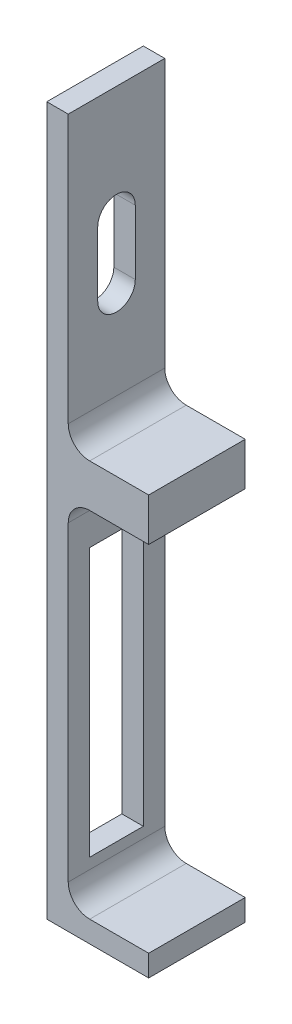
SolidWorks part; units mm, degrees
material "ПВХ Жесткий"
ref_plane "Спереди" through (0, 0, 0) normal (0, 0, 1) x (1, 0, 0)
ref_plane "Сверху" through (0, 0, 0) normal (0, 1, 0) x (1, 0, 0)
ref_plane "Справа" through (0, 0, 0) normal (1, 0, 0) x (0, 0, -1)
sketch "Эскиз1" plane through (0, 0, 0) normal (0, 0, 1) x (1, 0, 0)
  line L0 (0, 0) -> (9.5, 0)
  line L1 (9.5, 0) -> (9.5, 2)
  line L2 (9.5, 2) -> (2, 2)
  line L3 (2, 2) -> (2, 66)
  line L4 (2, 66) -> (0, 66)
  line L5 (0, 66) -> (0, 0)
  dimension "D1" = 2
  dimension "D2" = 66
  dimension "D3" = 9.5
extrude "Бобышка-Вытянуть1" add sketch "Эскиз1" along normal blind 9
sketch "Эскиз2" plane through (2, 0, 0) normal (1, 0, 0) x (0, 0, -1)
  line L0 (-4.5, 66) -> (-4.5, 2) construction
  line L1 (-9, 66) -> (0, 66) construction
  line L2 (-9, 2) -> (0, 2) construction
ref_plane "Плоскость1" through (0, 0, 4.5) normal (0, 0, 1) x (0, -1, 0)
sketch "Эскиз3" plane through (0, 0, 0) normal (-1, 0, 0) x (0, 0, 1)
  line L0 (9, 66) -> (0, 66) construction
  line L1 (4.5, 66) -> (4.5, 2) construction
  line L2 (4.5, 66) -> (4.5, 2) construction
  circle A1 centre (4.5, 52.52) radius 1.75
  dimension "D1" = 13.48
  dimension "D2" = 3.5
sketch "Эскиз4" plane through (0, 0, 0) normal (-1, 0, 0) x (0, 0, 1)
  line L0 (4.5, 55.52) -> (4.5, 49.52) construction
  line L1 (6.25, 55.52) -> (6.25, 49.52)
  line L2 (2.75, 55.52) -> (2.75, 49.52)
  line L3 (4.5, 66) -> (4.5, 43.3234) construction
  line L4 (9, 66) -> (0, 66) construction
  circle A0 centre (4.5, 52.52) radius 1.75 construction
  circle A1 centre (4.5, 52.52) radius 1.75 construction
  arc A2 (6.25, 55.52) -> (2.75, 55.52) centre (4.5, 55.52) ccw
  arc A3 (2.75, 49.52) -> (6.25, 49.52) centre (4.5, 49.52) ccw
  point P5 (4.5, 52.52)
  dimension "D1" = 6
extrude "Вырез-Вытянуть2" cut sketch "Эскиз4" against normal through all
sketch "Эскиз5" plane through (0, 0, 9) normal (0, 0, 1) x (1, 0, 0)
  line L0 (2, 2) -> (2, 66) construction
  line L1 (9.5, 2) -> (2, 2) construction
  line L2 (2, 2) -> (2, 9)
  line L3 (9.5, 2) -> (2, 2)
  line L4 (9.5, 2) -> (2, 9)
  dimension "D1" = 7
sketch "Эскиз6" plane through (2, 0, 0) normal (1, 0, 0) x (0, 0, -1)
  line L0 (-7, 5) -> (-2, 5)
  line L1 (-7, 5) -> (-7, 30)
  line L2 (-2, 5) -> (-2, 30)
  line L3 (-7, 30) -> (-2, 30)
  line L4 (-4.5, 30) -> (-4.5, 5) construction
  line L5 (-4.5, 66) -> (-4.5, 2) construction
  line L6 (-9, 2) -> (-9, 66) construction
  line L7 (-9, 2) -> (0, 2) construction
  dimension "D1" = 2
  dimension "D2" = 3
  dimension "D3" = 25
extrude "Вырез-Вытянуть3" cut sketch "Эскиз6" against normal through all
fillet "Скругление1" radius 2 1 edges at (2, 2, 4.5)
sketch "Эскиз7" plane through (0, 0, 9) normal (0, 0, 1) x (1, 0, 0)
  line L0 (2, 39) -> (2, 35)
  line L1 (2, 39) -> (9.5, 39)
  line L2 (2, 35) -> (9.5, 35)
  line L3 (9.5, 39) -> (9.5, 35)
  line L4 (2, 4) -> (2, 66) construction
  line L5 (0, 0) -> (9.5, 0) construction
  line L6 (9.5, 0) -> (9.5, 2) construction
  dimension "D1" = 35
  dimension "D2" = 4
extrude "Бобышка-Вытянуть2" add sketch "Эскиз7" against normal up to surface (9 mm away) up to face at (3.798, 19.9408, 0)
fillet "Скругление2" radius 2 2 edges at (2, 39, 4.5) (2, 35, 4.5)
